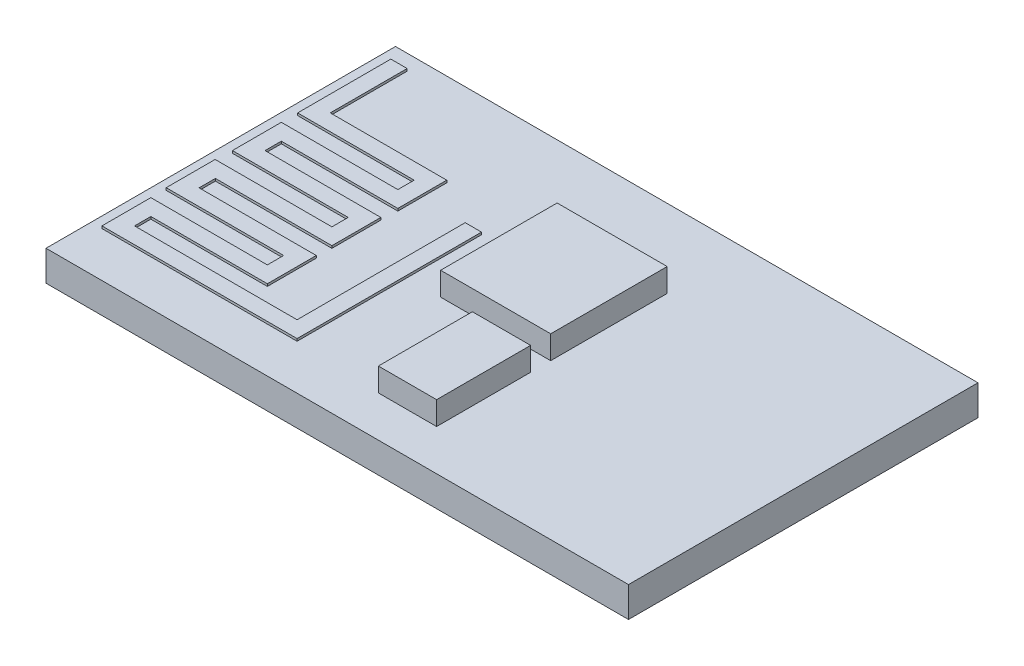
SolidWorks part; units mm, degrees
ref_plane "Front Plane" through (0, 0, 0) normal (0, 0, 1) x (1, 0, 0)
ref_plane "Top Plane" through (0, 0, 0) normal (0, 1, 0) x (1, 0, 0)
ref_plane "Right Plane" through (0, 0, 0) normal (1, 0, 0) x (0, 0, -1)
sketch "Sketch1" plane through (0, 0, 0) normal (0, 1, 0) x (1, 0, 0)
  line L1 (-12.5, 7.5) -> (12.5, 7.5)
  line L2 (-12.5, 7.5) -> (-12.5, -7.5)
  line L3 (-12.5, -7.5) -> (12.5, -7.5)
  line L4 (12.5, 7.5) -> (12.5, -7.5)
  line L5 (-12.5, 7.5) -> (12.5, -7.5) construction
  line L6 (-12.5, -7.5) -> (12.5, 7.5) construction
  point P0 (0, 0)
  dimension "D1" = 15
  dimension "D2" = 25
extrude "Boss-Extrude1" add sketch "Sketch1" along normal blind 1.3
sketch "Sketch2" plane through (0, 1.3, 0) normal (0, 1, 0) x (1, 0, 0)
  line L0 (-3.6547, -5.5693) -> (-12.0308, -5.5693)
  line L1 (-3.6547, -5.5693) -> (-3.6547, 2.3462)
  line L2 (-3.6547, 2.3462) -> (-4.3547, 2.3462)
  line L3 (-4.3547, 2.3462) -> (-4.3547, -4.8693)
  line L4 (-4.3547, -4.8693) -> (-11.3308, -4.8693)
  line L5 (-11.3308, -4.8693) -> (-11.3308, -4.1693)
  line L6 (-11.3308, -4.1693) -> (-6.3308, -4.1693)
  line L7 (-6.3308, -4.1693) -> (-6.3308, -2.0693)
  line L8 (-6.3308, -2.0693) -> (-11.3605, -2.0693)
  line L9 (-11.3605, -2.0693) -> (-11.3605, -1.3693)
  line L10 (-11.3605, -1.3693) -> (-6.3605, -1.3693)
  line L11 (-6.3605, -1.3693) -> (-6.3605, 0.7307)
  line L12 (-6.3605, 0.7307) -> (-11.3308, 0.7307)
  line L13 (-11.3308, 0.7307) -> (-11.3308, 1.4307)
  line L15 (-12.0308, -5.5693) -> (-12.0308, -3.4693)
  line L16 (-12.0308, -3.4693) -> (-7.0308, -3.4693)
  line L17 (-7.0308, -3.4693) -> (-7.0308, -2.7693)
  line L18 (-7.0308, -2.7693) -> (-12.0717, -2.7693)
  line L19 (-12.0717, -2.7693) -> (-12.0717, -0.6693)
  line L20 (-12.0717, -0.6693) -> (-7.0605, -0.6693)
  line L21 (-7.0605, -0.6693) -> (-7.0605, 0.0307)
  line L22 (-7.0605, 0.0307) -> (-12.0308, 0.0307)
  line L23 (-12.0308, 0.0307) -> (-12.0308, 2.1307)
  line L24 (-12.0308, 2.1307) -> (-7.0308, 2.1307)
  line L25 (-7.0308, 2.1307) -> (-7.0308, 2.8307)
  line L26 (-7.0308, 2.8307) -> (-12.0308, 2.8307)
  line L27 (-12.0308, 2.8307) -> (-12.0308, 6.8307)
  line L28 (-12.0308, 6.8307) -> (-11.3308, 6.8307)
  line L29 (-11.3308, 6.8307) -> (-11.3308, 3.5307)
  line L30 (-11.3308, 3.5307) -> (-6.3308, 3.5307)
  line L31 (-6.3308, 3.5307) -> (-6.3308, 1.4307)
  line L32 (-6.3308, 1.4307) -> (-11.3308, 1.4307)
  dimension "D1" = 0.7
  dimension "D2" = 0.7
  dimension "D3" = 0.7
  dimension "D4" = 0.7
  dimension "D5" = 0.7
  dimension "D6" = 0.7
  dimension "D7" = 0.7
  dimension "D8" = 0.7
  dimension "D9" = 0.7
  dimension "D10" = 0.7
  dimension "D11" = 0.7
  dimension "D12" = 0.7
  dimension "D13" = 0.7
  dimension "D14" = 5
  dimension "D15" = 5
  dimension "D16" = 5
  dimension "D17" = 0.7
  dimension "D18" = 5
  dimension "D19" = 4
  dimension "D20" = 0.7
extrude "Boss-Extrude2" add sketch "Sketch2" along normal blind 0.1
sketch "Sketch3" plane through (0, 1.3, 0) normal (0, 1, 0) x (1, 0, 0)
  line L1 (-2.2143, 4.1512) -> (2.5095, 4.1512)
  line L2 (-2.2143, 4.1512) -> (-2.2143, -0.8488)
  line L3 (-2.2143, -0.8488) -> (2.5095, -0.8488)
  line L4 (2.5095, 4.1512) -> (2.5095, -0.8488)
  line L5 (-2.2143, 4.1512) -> (2.5095, -0.8488) construction
  line L6 (-2.2143, -0.8488) -> (2.5095, 4.1512) construction
  line L7 (0.0095, -1.7099) -> (2.5095, -1.7099)
  line L8 (0.0095, -1.7099) -> (0.0095, -5.7448)
  line L9 (0.0095, -5.7448) -> (2.5095, -5.7448)
  line L10 (2.5095, -1.7099) -> (2.5095, -5.7448)
  line L11 (0.0095, -1.7099) -> (2.5095, -5.7448) construction
  line L12 (0.0095, -5.7448) -> (2.5095, -1.7099) construction
  point P0 (0.1476, 1.6512)
  point P5 (1.2595, -3.7273)
  dimension "D1" = 5
  dimension "D2" = 2.5
extrude "Boss-Extrude3" add sketch "Sketch3" along normal blind 1
sketch "Sketch4" plane through (0, 1.3, 0) normal (0, 1, 0) x (1, 0, 0)
  circle A0 centre (7.6087, 4.6312) radius 0.75
  circle A1 centre (10.5176, 4.6312) radius 0.75
  point P4 (0, 0)
  dimension "D1" = 1.5
  dimension "D2" = 1.5
